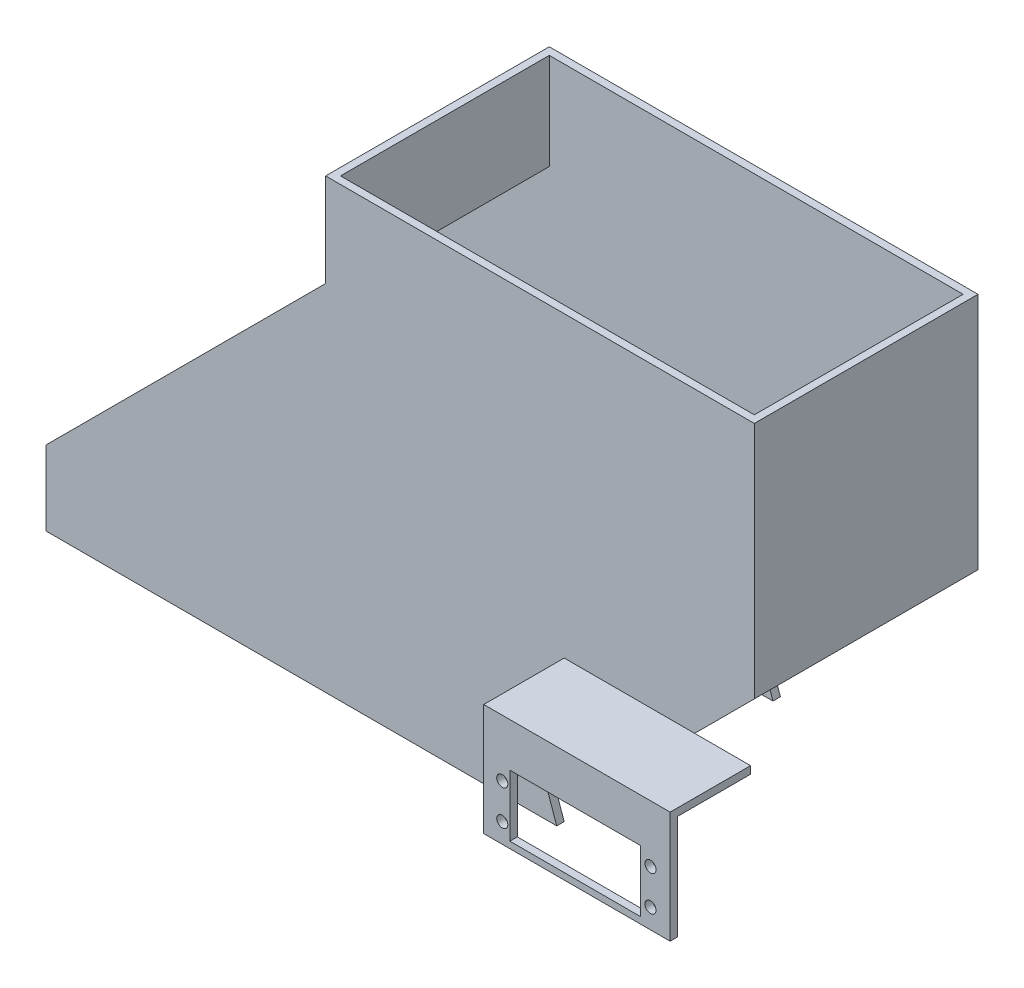
SolidWorks part; units mm, degrees
ref_plane "Front Plane" through (0, 0, 0) normal (0, 0, 1) x (1, 0, 0)
ref_plane "Top Plane" through (0, 0, 0) normal (0, 1, 0) x (1, 0, 0)
ref_plane "Right Plane" through (0, 0, 0) normal (1, 0, 0) x (0, 0, -1)
sketch "Sketch2" plane through (0, 0, 0) normal (0, 1, 0) x (1, 0, 0)
  line L1 (-77, -30) -> (77, -30)
  line L2 (-77, -30) -> (-77, 30)
  line L3 (-77, 30) -> (77, 30)
  line L4 (77, -30) -> (77, 30)
  line L5 (-77, -30) -> (77, 30) construction
  line L6 (-77, 30) -> (77, -30) construction
  line L7 (-75, -28) -> (75, -28)
  line L8 (-75, -28) -> (-75, 28)
  line L9 (-75, 28) -> (75, 28)
  line L10 (75, -28) -> (75, 28)
  line L11 (-75, -28) -> (75, 28) construction
  line L12 (-75, 28) -> (75, -28) construction
  point P0 (0, 0)
  point P6 (0, 0)
  dimension "D1" = 2
  dimension "D2" = 2
  dimension "D3" = 154
  dimension "D4" = 60
sketch "Sketch8" plane through (0, 0, 0) normal (0, 0, 1) x (1, 0, 0)
  line L0 (77, 0) -> (113, 36)
  line L1 (113, 36) -> (113, 100)
  line L2 (113, 100) -> (-2, 100)
  line L3 (-2, 100) -> (-2, 75)
  line L4 (-2, 75) -> (-77, 0)
  line L5 (54, 0) -> (77, 0)
  line L6 (-77, 0) -> (-77, -20)
  line L7 (-77, -20) -> (60, -20)
  line L8 (54, -3) -> (54, 0)
  line L9 (54, -3) -> (60, -20)
  dimension "D1" = 77
  dimension "D2" = 154
  dimension "D3" = 100
  dimension "D4" = 45
  dimension "D5" = 115
  dimension "D6" = 25
  dimension "D7" = 137
  dimension "D8" = 20
  dimension "D9" = 131
  dimension "D10" = 3
  dimension "D11" = 120
extrude "Boss-Extrude3" add sketch "Sketch8" along normal mid plane 60
shell "Shell1" thickness 2
ref_plane "Plane1" through (87, 0, 0) normal (1, 0, 0) x (0, 0, -1)
sketch "Sketch4" plane through (87, 0, 0) normal (1, 0, 0) x (0, 0, -1)
  line L0 (-30, 20) -> (-30, 18)
  line L2 (-30, 18) -> (-49.58, 18)
  line L3 (-49.58, 18) -> (-49.58, -10)
  line L4 (-49.58, -10) -> (-51.58, -10)
  line L5 (-51.58, -10) -> (-51.58, 20)
  line L6 (-51.58, 20) -> (-30, 20)
  line L8 (-30, 0) -> (30, 0) construction
  line L9 (-30, 0) -> (-30, 36) construction
  dimension "D1" = 2
  dimension "D2" = 2
  dimension "D3" = 19.58
  dimension "D4" = 20
  dimension "D5" = 30
extrude "Boss-Extrude2" add sketch "Sketch4" along normal mid plane 50
sketch "Sketch5" plane through (0, 0, 49.58) normal (0, 0, -1) x (-1, 0, 0)
  line L0 (-104.0037, 8.25) -> (-104.0037, -8.25)
  line L1 (-104.0037, -8.25) -> (-69.0037, -8.25)
  line L2 (-69.0037, -8.25) -> (-69.0037, 8.25)
  line L3 (-69.0037, 8.25) -> (-104.0037, 8.25)
  line L4 (-112, -10) -> (-112, 18) construction
  line L5 (-112, -10) -> (-62, -10) construction
  dimension "D1" = 35
  dimension "D2" = 7.9963
  dimension "D3" = 16.5
  dimension "D4" = 1.75
extrude "Cut-Extrude1" cut sketch "Sketch5" against normal up to next
sketch "Sketch6" plane through (0, 0, 51.58) normal (0, 0, 1) x (1, 0, 0)
  line L0 (62, 20) -> (62, -10) construction
  line L1 (112, 20) -> (62, 20) construction
  line L3 (86.8456, -10) -> (86.8456, 17.3094) construction
  line L4 (112, -10) -> (62, -10) construction
  line L6 (62.5751, 0) -> (110.5177, 0) construction
  circle A0 centre (66.9686, 4.7238) radius 1.4861
  circle A1 centre (106.7226, 4.7238) radius 1.4861
  circle A2 centre (106.7226, -4.7238) radius 1.4861
  circle A3 centre (66.9686, -4.7238) radius 1.4861
  dimension "D3" = 2.9723
  dimension "D1" = 4.9686
  dimension "D2" = 15.2762
  dimension "D4" = 24.8456
extrude "Cut-Extrude2" cut sketch "Sketch6" against normal up to next
